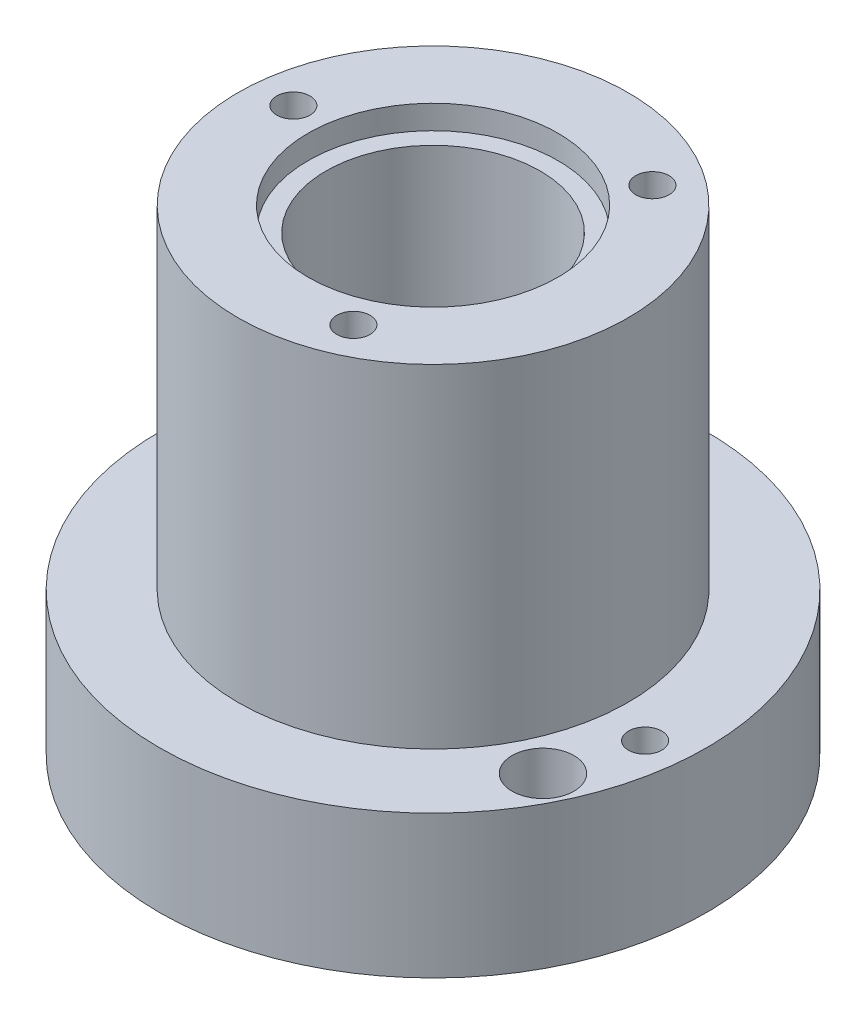
SolidWorks part; units mm, degrees
material "Copper"
ref_plane "Front Plane" through (0, 0, 0) normal (0, 0, 1) x (1, 0, 0)
ref_plane "Top Plane" through (0, 0, 0) normal (0, 1, 0) x (1, 0, 0)
ref_plane "Right Plane" through (0, 0, 0) normal (1, 0, 0) x (0, 0, -1)
sketch "Sketch1" plane through (0, 0, 0) normal (0, 1, 0) x (1, 0, 0)
  circle A0 centre (13.0282, -14.383) radius 14.605
  dimension "D1" = 29.21
extrude "Boss-Extrude2" add sketch "Sketch1" along normal blind 25.4 contours A0
ref_point "Point2"
sketch "Sketch10" plane through (0, 25.4, 0) normal (0, 1, 0) x (1, 0, 0)
  circle A0 centre (13.0282, -14.383) radius 5.715
  dimension "D1" = 11.43
extrude "Cut-Extrude5" cut sketch "Sketch10" against normal through all
sketch "Sketch11" plane through (0, 25.4, 0) normal (0, 1, 0) x (1, 0, 0)
  circle A0 centre (13.0282, -14.383) radius 6.6675
  dimension "D1" = 13.335
extrude "Cut-Extrude6" cut sketch "Sketch11" against normal blind 1.27
sketch "Sketch12" plane through (0, 25.4, 0) normal (0, 1, 0) x (1, 0, 0)
  circle A0 centre (13.0282, -14.383) radius 10.414
  dimension "D1" = 20.828
extrude "Cut-Extrude7" cut sketch "Sketch12" against normal blind 17.78 flip side to cut
sketch "Sketch13" plane through (0, 25.4, 0) normal (0, 1, 0) x (1, 0, 0)
  line L0 (13.0282, -14.383) -> (4.6924, -13.5041)
  dimension "D1" = 8.382
hole_wizard "#50 (0.07) Diameter Hole1" positions "Sketch16" profile "Sketch17" hole size "#50" standard "ANSI Inch"
sketch "Sketch16" plane through (0, 25.4, 0) normal (0, 1, 0) x (1, 0, 0)
  point P0 (4.6924, -13.5041)
sketch "Sketch17" plane through (4.6924, 25.4, 13.5041) normal (1, 0, 0) x (0, 0, 1)
  line L0 (0, 0) -> (0, 3.0742)
  line L1 (0, 3.0742) -> (0.889, 2.54)
  line L2 (0.889, 2.54) -> (0.889, 0)
  line L5 (0.889, 0) -> (0, 0)
  line L10 (0, 3.0742) -> (-0.889, 2.54) construction
  line L11 (0, -6.35) -> (0, 107.95) construction
  dimension "Hole Dia." = 1.778
  dimension "Hole Depth" = 2.54
  dimension "Drill Angle" = 118
pattern_circular "CirPattern1" count 3 over 360 about axis through (13.0282, 0, 14.383) along (0, 1, 0) of "#50 (0.07) Diameter Hole1"
sketch "Sketch18" plane through (0, 0, 0) normal (0, -1, 0) x (-1, 0, 0)
  line L0 (-13.0282, -14.383) -> (-8.1633, -24.3882)
  line L1 (-13.0282, -14.383) -> (-1.6068, -8.8295)
  line L2 (-13.0282, -14.383) -> (-0.3961, -13.0708)
  dimension "D1" = 11.1252
  dimension "D2" = 12.7
  dimension "D3" = 12.7
hole_wizard "Tap Drill for #6-32 Tap1" positions "Sketch23" profile "Sketch24" hole size "#6-32" standard "ANSI Inch"
sketch "Sketch23" plane through (0, 0, 0) normal (0, -1, 0) x (-1, 0, 0)
  point P0 (-8.1633, -24.3882)
sketch "Sketch24" plane through (8.1633, 0, 24.3882) normal (1, 0, 0) x (0, 0, -1)
  line L0 (0, 0) -> (0, 4.8132)
  line L1 (0, 4.8132) -> (1.3525, 4.0005)
  line L2 (1.3525, 4.0005) -> (1.3525, 0)
  line L5 (1.3525, 0) -> (0, 0)
  line L10 (0, 4.8132) -> (-1.3526, 4.0005) construction
  line L11 (0, -6.35) -> (0, 107.95) construction
  dimension "Hole Dia." = 2.7051
  dimension "Hole Depth" = 4.0005
  dimension "Drill Angle" = 118
pattern_circular "CirPattern2" count 2 every 180 about axis through (13.0282, 0, 14.383) along (0, 1, 0) of "Tap Drill for #6-32 Tap1"
sketch "Sketch26" plane through (0, 0, 0) normal (0, -1, 0) x (-1, 0, 0)
  circle A0 centre (-1.6068, -8.8295) radius 1.651
  dimension "D1" = 3.302
extrude "Cut-Extrude8" cut sketch "Sketch26" against normal blind 8.89
pattern_circular "CirPattern3" count 2 every 180 about axis through (13.0282, 0, 14.383) along (0, 1, 0) of "Cut-Extrude8"
sketch "Sketch27" plane through (0, 0, 0) normal (0, -1, 0) x (-1, 0, 0)
  circle A0 centre (-5.8274, -17.1427) radius 0.7938
  dimension "D1" = 1.5875
extrude "Cut-Extrude9" cut sketch "Sketch27" against normal blind 24.13 contours A0
sketch "Sketch30" plane through (0, 0, 0) normal (0, -1, 0) x (-1, 0, 0)
  line L0 (-5.8274, -17.1427) -> (-5.8274, -15.2377)
  line L1 (-5.8274, -17.1427) -> (-5.8274, -19.0477)
  dimension "D1" = 1.905
  dimension "D2" = 1.905
hole_wizard "Tap Drill for #0-80 Tap3" positions "Sketch31" profile "Sketch32" hole size "#0-80" standard "ANSI Inch"
sketch "Sketch31" plane through (0, 0, 0) normal (0, -1, 0) x (-1, 0, 0)
  point P0 (-5.8274, -15.2377)
  point P3 (-5.8274, -19.0477)
sketch "Sketch32" plane through (5.8274, 0, 15.2377) normal (1, 0, 0) x (0, 0, -1)
  line L0 (0, 0) -> (0, 6.8498)
  line L1 (0, 6.8498) -> (0.5956, 6.35)
  line L2 (0.5956, 6.35) -> (0.5956, 0)
  line L5 (0.5956, 0) -> (0, 0)
  line L10 (0, 6.8498) -> (-0.5956, 6.35) construction
  line L11 (0, -6.35) -> (0, 107.95) construction
  dimension "Hole Dia." = 1.1913
  dimension "Hole Depth" = 6.35
  dimension "Drill Angle" = 100
hole_wizard "Tap Drill for #2-56 Tap1" positions "3DSketch1" profile "Sketch34" hole size "#2-56" standard "ANSI Inch" end condition up to next
sketch3d "3DSketch1"
  point P0 (0.3961, 0, 13.0708)
sketch "Sketch34" plane through (0.3961, 0, 13.0708) normal (1, 0, 0) x (0, 0, -1)
  line L0 (0, 0) -> (0, 7.62)
  line L1 (0, 7.62) -> (0.889, 7.62)
  line L2 (0.889, 7.62) -> (0.889, 0)
  line L5 (0.889, 0) -> (0, 0)
  line L11 (0, -6.35) -> (0, 107.95) construction
  dimension "Thru Hole Dia." = 1.778
  dimension "Thru Hole Depth" = 7.62
pattern_circular "CirPattern4" count 2 every 180 about axis through (13.0282, 0, 14.383) along (0, 1, 0) of "Tap Drill for #2-56 Tap1"
